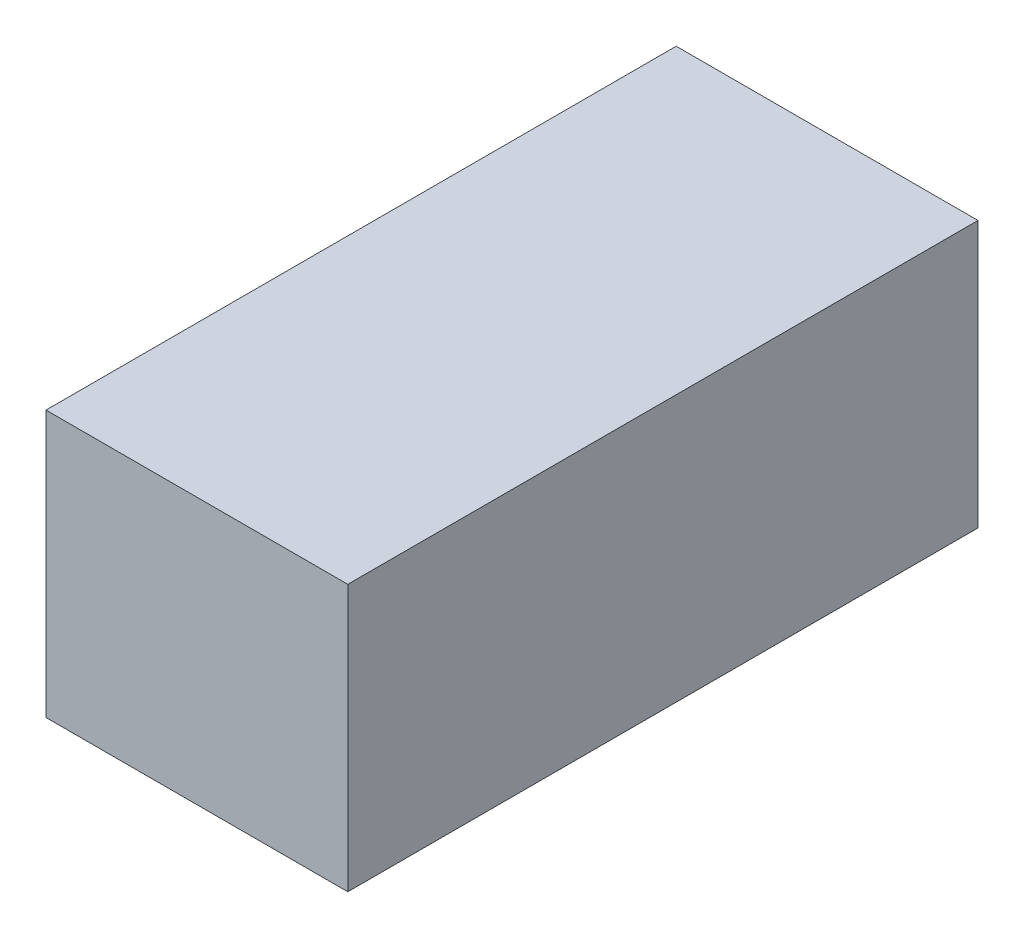
SolidWorks part; units mm, degrees
material "5052-H34"
ref_plane "Front Plane" through (0, 0, 0) normal (0, 0, 1) x (1, 0, 0)
ref_plane "Top Plane" through (0, 0, 0) normal (0, 1, 0) x (1, 0, 0)
ref_plane "Right Plane" through (0, 0, 0) normal (1, 0, 0) x (0, 0, -1)
sketch "Sketch1" plane through (0, 0, 0) normal (0, 0, 1) x (1, 0, 0)
  line L1 (0, 0) -> (34, 0)
  line L2 (0, 0) -> (0, 30)
  line L3 (0, 30) -> (34, 30)
  line L4 (34, 0) -> (34, 30)
  dimension "D1" = 34
  dimension "D2" = 30
extrude "Boss-Extrude1" add sketch "Sketch1" along normal blind 71
